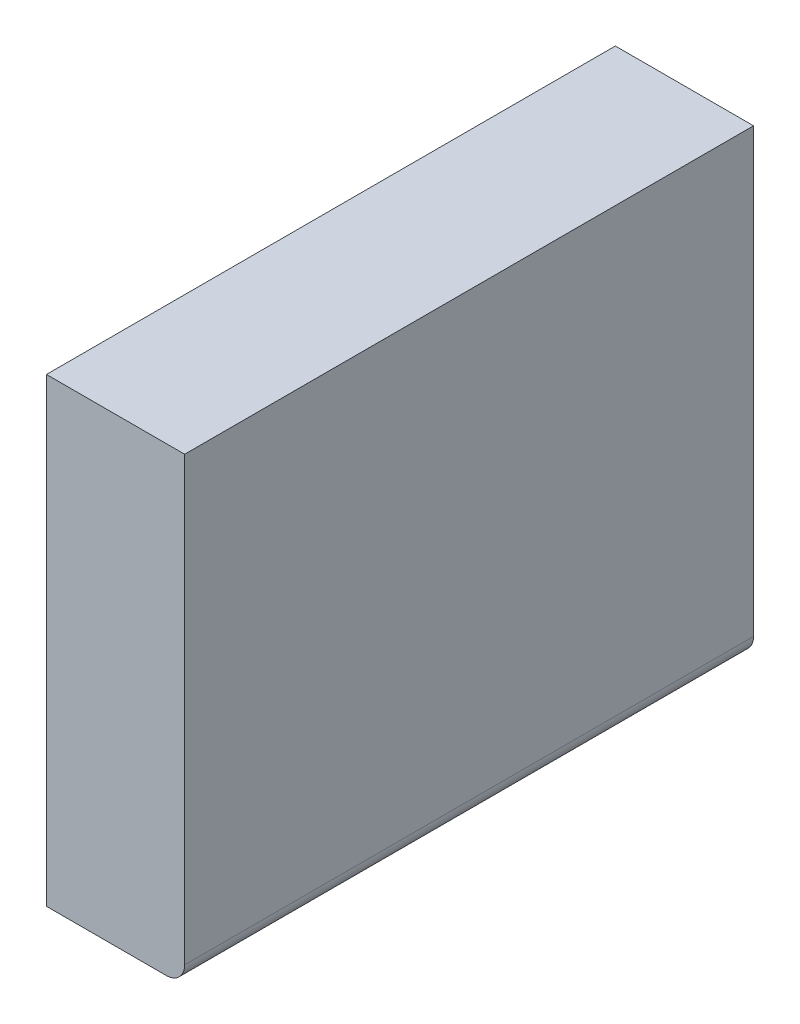
SolidWorks part; units mm, degrees
material "K110"
ref_plane "Front Plane" through (0, 0, 0) normal (0, 0, 1) x (1, 0, 0)
ref_plane "Top Plane" through (0, 0, 0) normal (0, 1, 0) x (1, 0, 0)
ref_plane "Right Plane" through (0, 0, 0) normal (1, 0, 0) x (0, 0, -1)
sketch "Sketch1" plane through (0, 0, 0) normal (0, 0, 1) x (1, 0, 0)
  line L1 (-7.5, -50) -> (7.5, -50)
  line L2 (-7.5, -50) -> (-7.5, 0)
  line L3 (-7.5, 0) -> (7.5, 0)
  line L4 (7.5, -50) -> (7.5, 0)
  point P4 (0, 0)
  dimension "D1" = 15
  dimension "D2" = 50
extrude "Boss-Extrude1" add sketch "Sketch1" along normal mid plane 61.75
fillet "Fillet1" radius 2 1 edges at (7.5, -50, 0)
